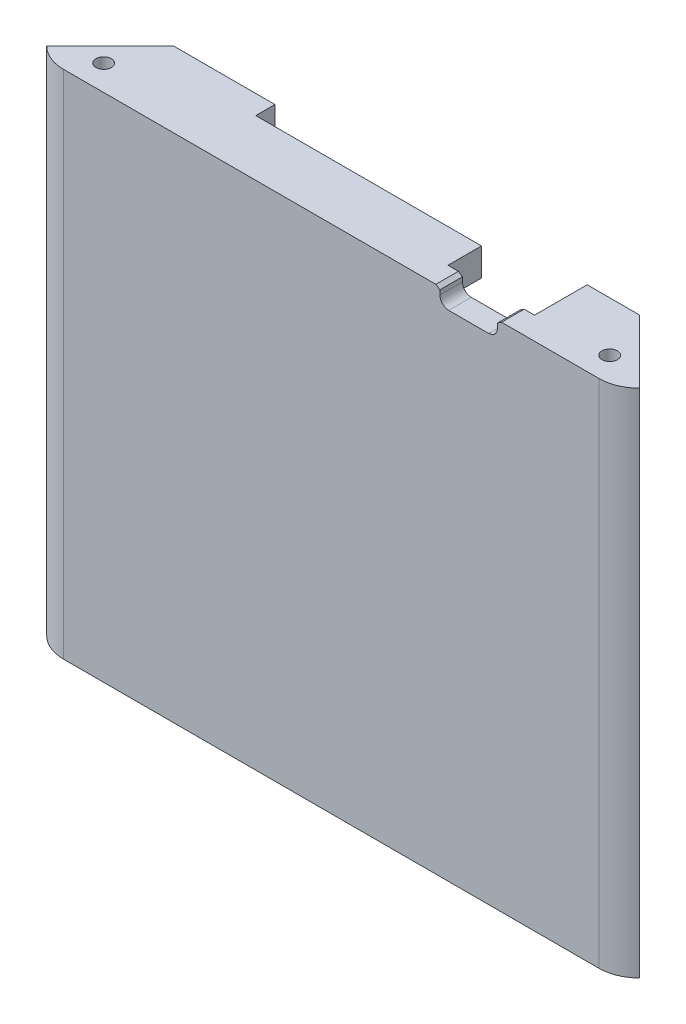
SolidWorks part; units mm, degrees
material "ПК/АБС"
ref_plane "Спереди" through (0, 0, 0) normal (0, 0, 1) x (1, 0, 0)
ref_plane "Сверху" through (0, 0, 0) normal (0, 1, 0) x (1, 0, 0)
ref_plane "Справа" through (0, 0, 0) normal (1, 0, 0) x (0, 0, -1)
sketch "Эскиз1" plane through (0, 0, 0) normal (0, 0, 1) x (1, 0, 0)
  line L1 (-40.95, 33.95) -> (40.95, 33.95)
  line L2 (-40.95, 33.95) -> (-40.95, -33.95)
  line L3 (-40.95, -33.95) -> (40.95, -33.95)
  line L4 (40.95, 33.95) -> (40.95, -33.95)
  point P0 (0, 0)
extrude "Бобышка-Вытянуть1" add sketch "Эскиз1" against normal blind 10
sketch "Эскиз2" plane through (0, 0, -10) normal (0, 0, -1) x (-1, 0, 0)
  line L1 (-30.25, 30.25) -> (30.25, 30.25)
  line L2 (-30.25, 30.25) -> (-30.25, -30.25)
  line L3 (-30.25, -30.25) -> (30.25, -30.25)
  line L4 (30.25, 30.25) -> (30.25, -30.25)
  line L5 (-30.25, 30.25) -> (30.25, -30.25) construction
  line L6 (-30.25, -30.25) -> (30.25, 30.25) construction
  point P0 (0, 0)
extrude "Вырез-Вытянуть1" cut sketch "Эскиз2" against normal blind 8.5
sketch "Эскиз3" plane through (0, 33.95, 0) normal (0, 1, 0) x (1, 0, 0)
  line L0 (30.95, 10) -> (40.95, 0)
  line L1 (-30.95, 10) -> (-40.95, 10)
  line L2 (-40.95, 10) -> (-40.95, 0)
  line L3 (0, 10) -> (0, 17.5402)
  line L4 (-40.95, 10) -> (40.95, 10) construction
  line L5 (40.95, 10) -> (40.95, 0)
  line L6 (30.95, 10) -> (40.95, 10)
  line L9 (-30.95, 10) -> (-40.95, 0)
sketch "Эскиз4" plane through (0, -33.95, -40.95) normal (0, 1, 0) x (1, 0, 0)
  line L2 (39.383, -39.383) -> (40.95, -40.95)
  line L3 (40.95, -40.95) -> (35.6, -40.95)
  line L4 (-40.95, -40.95) -> (-35.6, -40.95)
  line L5 (-39.383, -39.383) -> (-40.95, -40.95)
  arc A0 (35.6, -40.95) -> (39.383, -39.383) centre (35.6, -35.6) ccw
  arc A1 (-35.6, -40.95) -> (-39.383, -39.383) centre (-35.6, -35.6) cw
  point P0 (-40.95, -40.95)
extrude "Вырез-Вытянуть4" cut sketch "Эскиз4" along normal up to next
sketch "Эскиз5" plane through (0, 33.95, 0) normal (0, 1, 0) x (1, 0, 0)
  point P2 (33.6321, 3.3821)
  point P5 (-33.6321, 3.3821)
hole_wizard "Отверстие обработанное метчиком M2.5x0.451" positions "Эскиз7" profile "Эскиз8" tap size "M2.5x0.45" standard "Ansi Metric"
sketch "Эскиз7" plane through (0, 33.95, 0) normal (0, 1, 0) x (1, 0, 0)
  point P0 (33.6321, 3.3821)
  point P4 (-33.6321, 3.3821)
sketch "Эскиз8" plane through (33.6321, 33.95, -3.3821) normal (1, 0, 0) x (0, 0, 1)
  line L0 (0, 0) -> (0, 5.6159)
  line L1 (0, 5.6159) -> (1.025, 5)
  line L2 (1.025, 5) -> (1.025, 0)
  line L5 (1.025, 0) -> (0, 0)
  line L10 (0, 5.6159) -> (-1.025, 5) construction
  line L11 (0, -6.35) -> (0, 107.95) construction
  dimension "Диаметр сверла" = 2.05
  dimension "Глубина сверла" = 5
  dimension "Угол заточки сверла" = 118
cosmetic thread "Отверстие резьбы1" parameters "D1"=5, "D2"=2.5
cosmetic thread "Отверстие резьбы2" parameters "D1"=5, "D2"=2.5
mirror "Зеркальное отражение1" about plane through (0, 0, 0) normal (0, 1, 0) of "Отверстие обработанное метчиком M2.5x0.451"
extrude "Вырез-Вытянуть5" cut sketch "Эскиз3" against normal up to next
sketch "Эскиз10" plane through (0, 33.95, 0) normal (0, 1, 0) x (1, 0, 0)
  line L1 (24.0222, 3.0022) -> (12.5222, 3.0022)
  line L2 (24.0222, 3.0022) -> (24.0222, 10)
  line L3 (24.0222, 10) -> (12.5222, 10)
  line L4 (12.5222, 3.0022) -> (12.5222, 7.45)
  line L6 (12.5222, 10) -> (-17.4778, 10)
  line L7 (30.95, 10) -> (-30.95, 10) construction
  line L8 (-17.4778, 10) -> (-17.4778, 7.45)
  line L9 (-17.4778, 7.45) -> (12.5222, 7.45)
extrude "Вырез-Вытянуть6" cut sketch "Эскиз10" against normal up to next
sketch "Эскиз11" plane through (0, 0, 0) normal (0, 0, 1) x (1, 0, 0)
  line L7 (14.4372, 33.5712) -> (14.4372, 32.9766)
  line L8 (15.6138, 31.8) -> (20.9306, 31.8)
  line L9 (22.1072, 32.9766) -> (22.1072, 33.5915)
  line L10 (13.2168, 34.45) -> (23.3908, 34.45)
  spline S8 degree 3 poles (14.4372, 32.9766) (14.4511, 32.828) (14.5064, 32.5346) (14.7634, 32.1262) (15.1718, 31.8692) (15.4652, 31.8139) (15.6138, 31.8) knots -0.018209 -0.018209 -0.018209 -0.018209 0.240896 0.5 0.759104 1.018209 1.018209 1.018209 1.018209
  spline S9 degree 3 poles (20.9306, 31.8) (21.0791, 31.8139) (21.3726, 31.8692) (21.7809, 32.1262) (22.038, 32.5346) (22.0932, 32.828) (22.1072, 32.9766) knots -0.018209 -0.018209 -0.018209 -0.018209 0.240896 0.5 0.759104 1.018209 1.018209 1.018209 1.018209
  spline S10 degree 3 poles (22.1072, 33.5915) (22.5351, 33.8777) (22.9629, 34.1638) (23.3908, 34.45) knots 1.333302 1.333302 1.333302 1.333302 6.343818 6.343818 6.343818 6.343818
  spline S11 degree 3 poles (13.2168, 34.45) (13.6236, 34.1571) (14.0304, 33.8641) (14.4372, 33.5712) knots 1.296986 1.296986 1.296986 1.296986 5.968647 5.968647 5.968647 5.968647
extrude "Вырез-Вытянуть7" cut sketch "Эскиз11" against normal up to next
